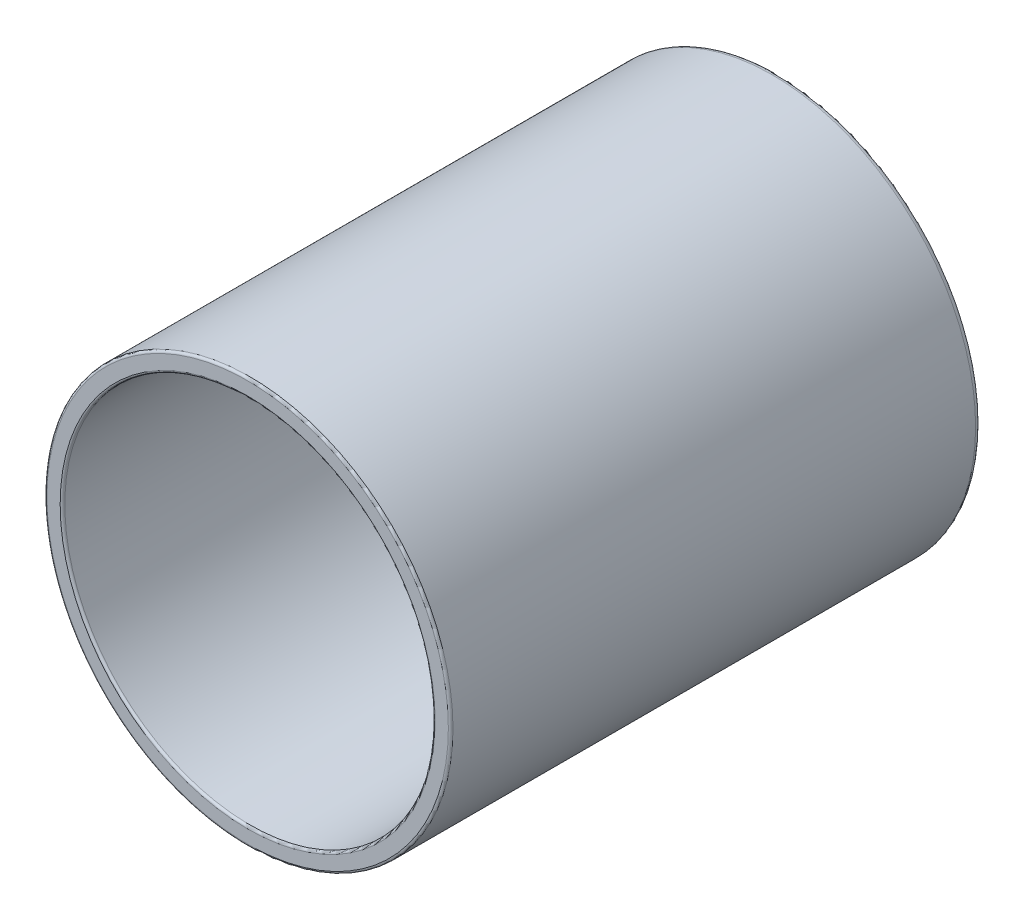
SolidWorks part; units mm, degrees
material "PET"
ref_plane "Plan de face" through (0, 0, 0) normal (0, 0, 1) x (1, 0, 0)
ref_plane "Plan de dessus" through (0, 0, 0) normal (0, 1, 0) x (1, 0, 0)
ref_plane "Plan de droite" through (0, 0, 0) normal (1, 0, 0) x (0, 0, -1)
sketch "Esquisse1" plane through (0, 0, 0) normal (0, 0, 1) x (1, 0, 0)
  circle A0 centre (-3.3056, 2.9802) radius 8.76
  dimension "D1" = 17.52
extrude "Boss.-Extru.1" add sketch "Esquisse1" along normal blind 22.9
shell "Coque1" thickness 0.77
fillet "Congé1" radius 0.25 1 edges at (4.6844, 2.9802, 0.77)
fillet "Congé2" radius 0.25 1 edges at (5.4544, 2.9802, 0)
fillet "Congé3" radius 0.1 2 edges at (5.4544, 2.9802, 22.9) (4.6844, 2.9802, 22.9)
